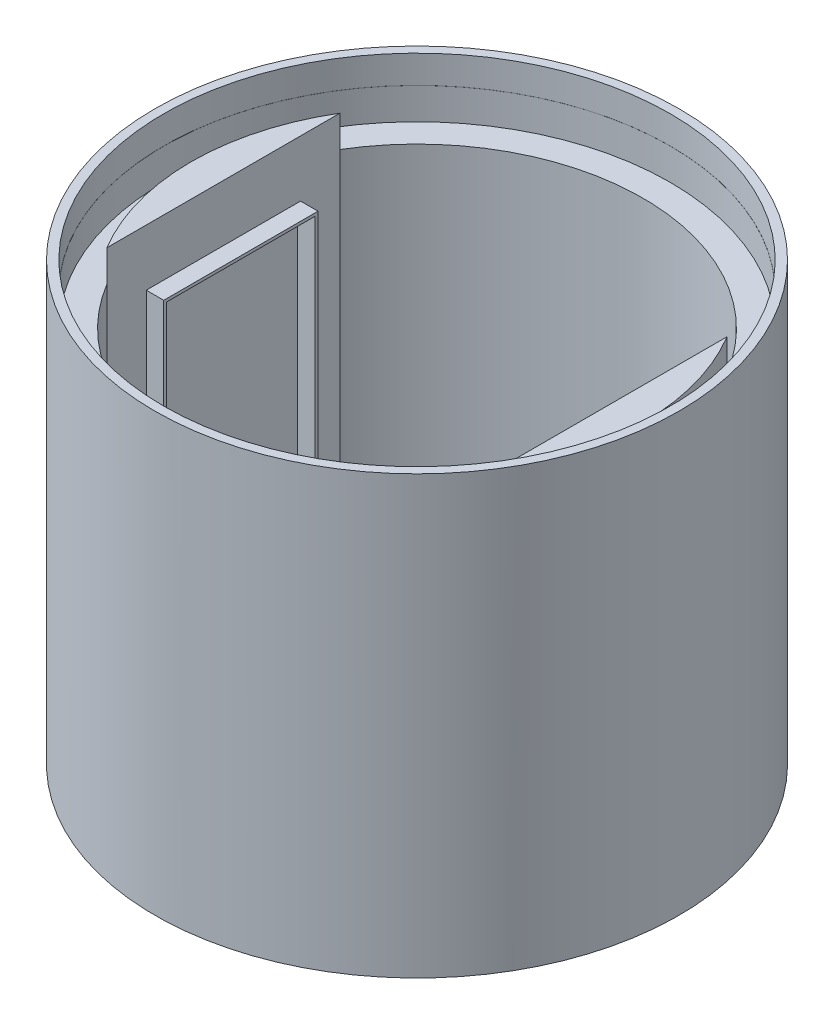
SolidWorks part; units mm, degrees
ref_plane "Front Plane" through (0, 0, 0) normal (0, 0, 1) x (1, 0, 0)
ref_plane "Top Plane" through (0, 0, 0) normal (0, 1, 0) x (1, 0, 0)
ref_plane "Right Plane" through (0, 0, 0) normal (1, 0, 0) x (0, 0, -1)
sketch "Sketch1" plane through (0, 0, 0) normal (0, 1, 0) x (1, 0, 0)
  circle A0 centre (0, 0) radius 45
  dimension "D1" = 90
extrude "Boss-Extrude1" add sketch "Sketch1" along normal blind 15
sketch "Sketch2" plane through (0, 15, 0) normal (0, 1, 0) x (1, 0, 0)
  circle A0 centre (0, 0) radius 43.5
  dimension "D1" = 87
extrude "Cut-Extrude1" cut sketch "Sketch2" against normal blind 4.8
sketch "Sketch3" plane through (0, 10.2, 0) normal (0, 1, 0) x (1, 0, 0)
  circle A0 centre (0, 0) radius 43.4879
  circle A1 centre (0, 0) radius 38.8
  dimension "D2" = 77.6
extrude "Cut-Extrude2" cut sketch "Sketch3" against normal blind 5.4
sketch "Sketch4" plane through (0, 0, 0) normal (0, -1, 0) x (1, 0, 0)
  circle A0 centre (0, 0) radius 45
extrude "Boss-Extrude2" add sketch "Sketch4" along normal blind 60
sketch "Sketch6" plane through (0, -60, 0) normal (0, -1, 0) x (1, 0, 0)
  circle A0 centre (0, 0) radius 8
  dimension "D1" = 16
extrude "Cut-Extrude4" cut sketch "Sketch6" against normal blind 71
sketch "Sketch10" plane through (0, 10.2, 0) normal (0, 1, 0) x (1, 0, 0)
  line L0 (-33.2482, 20) -> (-33.2482, -20)
  line L5 (0, 0) -> (0, 13.2297) construction
  line L6 (33.2482, 20) -> (33.2482, -20)
  circle A6 centre (0, 0) radius 38.8 construction
  arc A7 (-33.2482, -20) -> (33.2482, -20) centre (0, 0) ccw
  arc A8 (33.2482, 20) -> (-33.2482, 20) centre (0, 0) ccw
  dimension "D1" = 40
extrude "Cut-Extrude6" cut sketch "Sketch10" against normal blind 66
sketch "Sketch11" plane through (-33.2482, 0, 0) normal (1, 0, 0) x (0, 0, -1)
  line L1 (-12.75, 0) -> (12.75, 0)
  line L2 (-12.75, 0) -> (-12.75, -37.6)
  line L3 (-12.75, -37.6) -> (12.75, -37.6)
  line L4 (12.75, 0) -> (12.75, -37.6)
  line L10 (-13.25, 0.5) -> (13.25, 0.5)
  line L11 (13.25, 0.5) -> (13.25, -38.1)
  line L12 (-13.25, -38.1) -> (13.25, -38.1)
  line L13 (-13.25, 0.5) -> (-13.25, -38.1)
  point P4 (0, 0)
  dimension "D1" = 37.6
  dimension "D2" = 25.5
  dimension "D3" = 0.5
extrude "Boss-Extrude3" add sketch "Sketch11" along normal blind 3
mirror "Mirror1" about plane through (0, 0, 0) normal (1, 0, 0) of "Boss-Extrude3"
sketch "Sketch12" plane through (0, -55.8, 0) normal (0, 1, 0) x (1, 0, 0)
  line L0 (0, 0) -> (0, 3.7567) construction
  line L1 (-19.5091, 0) -> (19.5091, 0) construction
  line L2 (-26.5091, 7) -> (-19.5091, 7)
  line L3 (-26.5091, 7) -> (-26.5091, -7)
  line L4 (-26.5091, -7) -> (-19.5091, -7)
  line L5 (-19.5091, 7) -> (-19.5091, -7)
  line L6 (-26.5091, 7) -> (-19.5091, 7)
  line L7 (-26.5091, -7) -> (-19.5091, -7)
  line L8 (26.5091, -7) -> (19.5091, -7)
  line L9 (26.5091, 7) -> (19.5091, 7)
  line L10 (19.5091, 7) -> (19.5091, -7)
  line L11 (26.5091, -7) -> (19.5091, -7)
  line L12 (26.5091, 7) -> (26.5091, -7)
  line L13 (26.5091, 7) -> (19.5091, 7)
  dimension "D1" = 14
  dimension "D2" = 7
extrude "Cut-Extrude-Thin1" cut sketch "Sketch12" against normal blind 10 thin contours L5 | L12
sketch "Sketch13" plane through (0, -60, 0) normal (0, -1, 0) x (1, 0, 0)
  line L0 (0, 0) -> (0, 35) construction
  line L1 (0, 0) -> (11.9634, 0) construction
  circle A0 centre (0, 35) radius 2
  circle A1 centre (0, -35) radius 2
  dimension "D1" = 4
  dimension "D2" = 35
extrude "Cut-Extrude7" cut sketch "Sketch13" against normal blind 10
